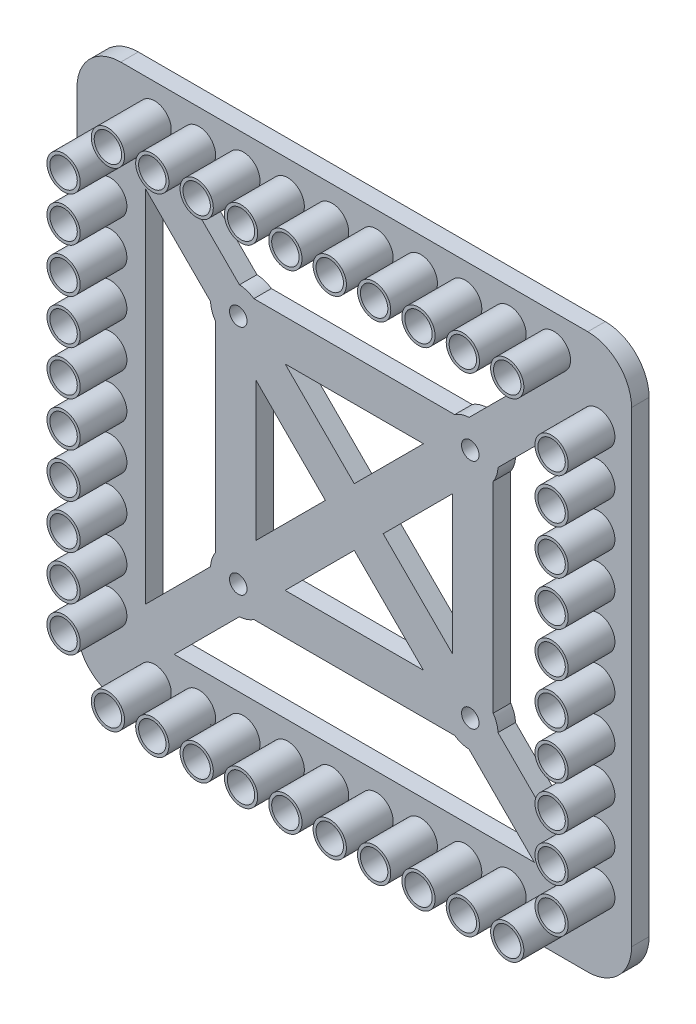
SolidWorks part; units mm, degrees
ref_plane "Front Plane" through (0, 0, 0) normal (0, 0, 1) x (1, 0, 0)
ref_plane "Top Plane" through (0, 0, 0) normal (0, 1, 0) x (1, 0, 0)
ref_plane "Right Plane" through (0, 0, 0) normal (1, 0, 0) x (0, 0, -1)
sketch "Sketch1" plane through (0, 0, 0) normal (0, 0, 1) x (1, 0, 0)
  line L0 (453.6808, -1249.6067) -> (438.4808, -1249.6067) construction
  line L1 (467.0808, -1278.2067) -> (577.0808, -1278.2067) construction
  line L2 (467.0808, -1278.2067) -> (467.0808, -1388.2067) construction
  line L3 (467.0808, -1388.2067) -> (577.0808, -1388.2067) construction
  line L4 (577.0808, -1278.2067) -> (577.0808, -1388.2067) construction
  line L5 (438.4808, -1264.8067) -> (438.4808, -1401.6067) construction
  line L6 (453.6808, -1249.6067) -> (590.4808, -1249.6067) construction
  line L7 (467.0808, -1388.2067) -> (577.0808, -1278.2067) construction
  line L8 (605.6808, -1401.6067) -> (605.6808, -1264.8067) construction
  line L9 (590.4808, -1416.8067) -> (453.6808, -1416.8067) construction
  line L10 (605.6808, -1401.6067) -> (605.6808, -1416.8067) construction
  line L12 (427.0808, -1238.2067) -> (617.0808, -1238.2067) construction
  line L13 (427.0808, -1238.2067) -> (427.0808, -1428.2067) construction
  line L14 (427.0808, -1428.2067) -> (617.0808, -1428.2067) construction
  line L15 (617.0808, -1238.2067) -> (617.0808, -1428.2067) construction
  line L16 (427.0808, -1238.2067) -> (617.0808, -1428.2067) construction
  line L17 (427.0808, -1428.2067) -> (617.0808, -1238.2067) construction
  circle A0 centre (453.6808, -1249.6067) radius 4.7
  circle A1 centre (453.6808, -1249.6067) radius 5.7
  circle A2 centre (468.8808, -1249.6067) radius 4.7
  circle A3 centre (468.8808, -1249.6067) radius 5.7
  circle A4 centre (484.0808, -1249.6067) radius 4.7
  circle A5 centre (484.0808, -1249.6067) radius 5.7
  circle A6 centre (499.2808, -1249.6067) radius 4.7
  circle A7 centre (499.2808, -1249.6067) radius 5.7
  circle A8 centre (514.4808, -1249.6067) radius 4.7
  circle A9 centre (514.4808, -1249.6067) radius 5.7
  circle A10 centre (529.6808, -1249.6067) radius 4.7
  circle A11 centre (529.6808, -1249.6067) radius 5.7
  circle A12 centre (544.8808, -1249.6067) radius 4.7
  circle A13 centre (544.8808, -1249.6067) radius 5.7
  circle A14 centre (560.0808, -1249.6067) radius 4.7
  circle A15 centre (560.0808, -1249.6067) radius 5.7
  circle A16 centre (575.2808, -1249.6067) radius 4.7
  circle A17 centre (575.2808, -1249.6067) radius 5.7
  circle A18 centre (590.4808, -1249.6067) radius 4.7
  circle A19 centre (590.4808, -1249.6067) radius 5.7
  circle A20 centre (438.4808, -1249.6067) radius 4.7 construction
  circle A21 centre (438.4808, -1249.6067) radius 5.7 construction
  circle A22 centre (438.4808, -1264.8067) radius 4.7
  circle A23 centre (438.4808, -1264.8067) radius 5.7
  circle A24 centre (438.4808, -1280.0067) radius 4.7
  circle A25 centre (438.4808, -1280.0067) radius 5.7
  circle A26 centre (438.4808, -1295.2067) radius 4.7
  circle A27 centre (438.4808, -1295.2067) radius 5.7
  circle A28 centre (438.4808, -1310.4067) radius 4.7
  circle A29 centre (438.4808, -1310.4067) radius 5.7
  circle A30 centre (438.4808, -1325.6067) radius 4.7
  circle A31 centre (438.4808, -1325.6067) radius 5.7
  circle A32 centre (438.4808, -1340.8067) radius 4.7
  circle A33 centre (438.4808, -1340.8067) radius 5.7
  circle A34 centre (438.4808, -1356.0067) radius 4.7
  circle A35 centre (438.4808, -1356.0067) radius 5.7
  circle A36 centre (438.4808, -1371.2067) radius 4.7
  circle A37 centre (438.4808, -1371.2067) radius 5.7
  circle A38 centre (438.4808, -1386.4067) radius 4.7
  circle A39 centre (438.4808, -1386.4067) radius 5.7
  circle A40 centre (438.4808, -1401.6067) radius 4.7
  circle A41 centre (438.4808, -1401.6067) radius 5.7
  circle A42 centre (605.6808, -1416.8067) radius 5.7 construction
  circle A43 centre (605.6808, -1416.8067) radius 4.7 construction
  circle A44 centre (453.6808, -1416.8067) radius 5.7
  circle A45 centre (453.6808, -1416.8067) radius 4.7
  circle A46 centre (468.8808, -1416.8067) radius 5.7
  circle A47 centre (468.8808, -1416.8067) radius 4.7
  circle A48 centre (484.0808, -1416.8067) radius 5.7
  circle A49 centre (484.0808, -1416.8067) radius 4.7
  circle A50 centre (499.2808, -1416.8067) radius 5.7
  circle A51 centre (499.2808, -1416.8067) radius 4.7
  circle A52 centre (514.4808, -1416.8067) radius 5.7
  circle A53 centre (514.4808, -1416.8067) radius 4.7
  circle A54 centre (529.6808, -1416.8067) radius 5.7
  circle A55 centre (529.6808, -1416.8067) radius 4.7
  circle A56 centre (544.8808, -1416.8067) radius 5.7
  circle A57 centre (544.8808, -1416.8067) radius 4.7
  circle A58 centre (560.0808, -1416.8067) radius 5.7
  circle A59 centre (560.0808, -1416.8067) radius 4.7
  circle A60 centre (575.2808, -1416.8067) radius 5.7
  circle A61 centre (575.2808, -1416.8067) radius 4.7
  circle A62 centre (590.4808, -1416.8067) radius 5.7
  circle A63 centre (590.4808, -1416.8067) radius 4.7
  circle A64 centre (605.6808, -1264.8067) radius 5.7
  circle A65 centre (605.6808, -1264.8067) radius 4.7
  circle A66 centre (605.6808, -1280.0067) radius 5.7
  circle A67 centre (605.6808, -1280.0067) radius 4.7
  circle A68 centre (605.6808, -1295.2067) radius 5.7
  circle A69 centre (605.6808, -1295.2067) radius 4.7
  circle A70 centre (605.6808, -1310.4067) radius 5.7
  circle A71 centre (605.6808, -1310.4067) radius 4.7
  circle A72 centre (605.6808, -1325.6067) radius 5.7
  circle A73 centre (605.6808, -1325.6067) radius 4.7
  circle A74 centre (605.6808, -1340.8067) radius 5.7
  circle A75 centre (605.6808, -1340.8067) radius 4.7
  circle A76 centre (605.6808, -1356.0067) radius 5.7
  circle A77 centre (605.6808, -1356.0067) radius 4.7
  circle A78 centre (605.6808, -1371.2067) radius 5.7
  circle A79 centre (605.6808, -1371.2067) radius 4.7
  circle A80 centre (605.6808, -1386.4067) radius 5.7
  circle A81 centre (605.6808, -1386.4067) radius 4.7
  circle A82 centre (605.6808, -1401.6067) radius 5.7
  circle A83 centre (605.6808, -1401.6067) radius 4.7
  point P4 (522.0808, -1249.6067)
  point P5 (522.0808, -1278.2067)
  point P10 (438.4808, -1333.2067)
  point P42 (467.0808, -1333.2067)
  point P136 (522.0808, -1333.2067)
  dimension "D5" = 9.4
  dimension "D6" = 1
  dimension "D1" = 110
  dimension "D2" = 110
  dimension "D3" = 190
  dimension "D4" = 136.8
  dimension "D8" = 11
  dimension "D9" = 136.8
  dimension "D10" = 190
  dimension "D7" = 10
extrude "Boss-Extrude1" add sketch "Sketch1" along normal blind 16
sketch "Sketch4" plane through (0, 0, 0) normal (0, 0, 1) x (1, 0, 0)
  line L0 (427.0808, -1238.2067) -> (617.0808, -1428.2067) construction
  line L1 (427.0808, -1428.2067) -> (617.0808, -1428.2067)
  line L2 (427.0808, -1428.2067) -> (427.0808, -1238.2067)
  line L3 (427.0808, -1238.2067) -> (617.0808, -1238.2067)
  line L4 (617.0808, -1428.2067) -> (617.0808, -1238.2067)
  line L5 (427.0808, -1428.2067) -> (617.0808, -1238.2067) construction
  line L6 (427.0808, -1238.2067) -> (617.0808, -1428.2067) construction
  circle A0 centre (438.4808, -1264.8067) radius 4.7 construction
  circle A1 centre (438.4808, -1280.0067) radius 4.7 construction
  circle A2 centre (438.4808, -1295.2067) radius 4.7 construction
  circle A3 centre (438.4808, -1310.4067) radius 4.7 construction
  circle A4 centre (438.4808, -1325.6067) radius 4.7 construction
  circle A5 centre (438.4808, -1340.8067) radius 4.7 construction
  circle A6 centre (438.4808, -1356.0067) radius 4.7 construction
  circle A7 centre (438.4808, -1371.2067) radius 4.7 construction
  circle A8 centre (438.4808, -1386.4067) radius 4.7 construction
  circle A9 centre (438.4808, -1401.6067) radius 4.7 construction
  circle A10 centre (453.6808, -1416.8067) radius 4.7 construction
  circle A11 centre (468.8808, -1416.8067) radius 4.7 construction
  circle A12 centre (484.0808, -1416.8067) radius 4.7 construction
  circle A13 centre (499.2808, -1416.8067) radius 4.7 construction
  circle A14 centre (514.4808, -1416.8067) radius 4.7 construction
  circle A15 centre (529.6808, -1416.8067) radius 4.7 construction
  circle A16 centre (544.8808, -1416.8067) radius 4.7 construction
  circle A17 centre (560.0808, -1416.8067) radius 4.7 construction
  circle A18 centre (575.2808, -1416.8067) radius 4.7 construction
  circle A19 centre (590.4808, -1416.8067) radius 4.7 construction
  circle A20 centre (605.6808, -1401.6067) radius 4.7 construction
  circle A21 centre (605.6808, -1386.4067) radius 4.7 construction
  circle A22 centre (605.6808, -1371.2067) radius 4.7 construction
  circle A23 centre (605.6808, -1356.0067) radius 4.7 construction
  circle A24 centre (605.6808, -1340.8067) radius 4.7 construction
  circle A25 centre (605.6808, -1325.6067) radius 4.7 construction
  circle A26 centre (605.6808, -1310.4067) radius 4.7 construction
  circle A27 centre (605.6808, -1295.2067) radius 4.7 construction
  circle A28 centre (605.6808, -1280.0067) radius 4.7 construction
  circle A29 centre (605.6808, -1264.8067) radius 4.7 construction
  circle A30 centre (590.4808, -1249.6067) radius 4.7 construction
  circle A31 centre (575.2808, -1249.6067) radius 4.7 construction
  circle A32 centre (560.0808, -1249.6067) radius 4.7 construction
  circle A33 centre (544.8808, -1249.6067) radius 4.7 construction
  circle A34 centre (529.6808, -1249.6067) radius 4.7 construction
  circle A35 centre (514.4808, -1249.6067) radius 4.7 construction
  circle A36 centre (499.2808, -1249.6067) radius 4.7 construction
  circle A37 centre (484.0808, -1249.6067) radius 4.7 construction
  circle A38 centre (468.8808, -1249.6067) radius 4.7 construction
  circle A39 centre (453.6808, -1249.6067) radius 4.7 construction
  circle A40 centre (438.4808, -1264.8067) radius 4.7
  circle A41 centre (438.4808, -1280.0067) radius 4.7
  circle A42 centre (438.4808, -1295.2067) radius 4.7
  circle A43 centre (438.4808, -1310.4067) radius 4.7
  circle A44 centre (438.4808, -1325.6067) radius 4.7
  circle A45 centre (438.4808, -1340.8067) radius 4.7
  circle A46 centre (438.4808, -1356.0067) radius 4.7
  circle A47 centre (438.4808, -1371.2067) radius 4.7
  circle A48 centre (438.4808, -1386.4067) radius 4.7
  circle A49 centre (438.4808, -1401.6067) radius 4.7
  circle A50 centre (453.6808, -1416.8067) radius 4.7
  circle A51 centre (468.8808, -1416.8067) radius 4.7
  circle A52 centre (484.0808, -1416.8067) radius 4.7
  circle A53 centre (499.2808, -1416.8067) radius 4.7
  circle A54 centre (514.4808, -1416.8067) radius 4.7
  circle A55 centre (529.6808, -1416.8067) radius 4.7
  circle A56 centre (544.8808, -1416.8067) radius 4.7
  circle A57 centre (560.0808, -1416.8067) radius 4.7
  circle A58 centre (575.2808, -1416.8067) radius 4.7
  circle A59 centre (590.4808, -1416.8067) radius 4.7
  circle A60 centre (605.6808, -1401.6067) radius 4.7
  circle A61 centre (605.6808, -1386.4067) radius 4.7
  circle A62 centre (605.6808, -1371.2067) radius 4.7
  circle A63 centre (605.6808, -1356.0067) radius 4.7
  circle A64 centre (605.6808, -1340.8067) radius 4.7
  circle A65 centre (605.6808, -1325.6067) radius 4.7
  circle A66 centre (605.6808, -1310.4067) radius 4.7
  circle A67 centre (605.6808, -1295.2067) radius 4.7
  circle A68 centre (605.6808, -1280.0067) radius 4.7
  circle A69 centre (605.6808, -1264.8067) radius 4.7
  circle A70 centre (590.4808, -1249.6067) radius 4.7
  circle A71 centre (575.2808, -1249.6067) radius 4.7
  circle A72 centre (560.0808, -1249.6067) radius 4.7
  circle A73 centre (544.8808, -1249.6067) radius 4.7
  circle A74 centre (529.6808, -1249.6067) radius 4.7
  circle A75 centre (514.4808, -1249.6067) radius 4.7
  circle A76 centre (499.2808, -1249.6067) radius 4.7
  circle A77 centre (484.0808, -1249.6067) radius 4.7
  circle A78 centre (468.8808, -1249.6067) radius 4.7
  circle A79 centre (453.6808, -1249.6067) radius 4.7
  point P0 (522.0808, -1333.2067)
extrude "Boss-Extrude3" add sketch "Sketch4" against normal blind 6
sketch "Sketch5" plane through (0, 0, 0) normal (0, 0, 1) x (1, 0, 0)
  circle A0 centre (482.3308, -1293.4567) radius 3
  circle A1 centre (561.8308, -1293.4567) radius 3
  circle A2 centre (561.8308, -1372.9567) radius 3
  circle A3 centre (482.3308, -1372.9567) radius 3
  point P11 (522.0808, -1333.2067)
  dimension "D1" = 6
  dimension "D2" = 4
extrude "Cut-Extrude1" cut sketch "Sketch5" against normal blind 6
sketch "Sketch7" plane through (0, 0, -6) normal (0, 0, -1) x (-1, 0, 0)
  line L6 (-617.0808, -1238.2067) -> (-427.0808, -1428.2067) construction
  line L7 (-617.0808, -1428.2067) -> (-427.0808, -1238.2067) construction
  line L8 (-612.1311, -1433.1565) -> (-422.1311, -1243.1565)
  line L9 (-450.4808, -1404.8067) -> (-593.6808, -1404.8067)
  line L10 (-450.4808, -1404.8067) -> (-450.4808, -1261.6067)
  line L11 (-450.4808, -1261.6067) -> (-593.6808, -1261.6067)
  line L12 (-593.6808, -1404.8067) -> (-593.6808, -1261.6067)
  line L13 (-450.4808, -1404.8067) -> (-593.6808, -1261.6067) construction
  line L14 (-450.4808, -1261.6067) -> (-593.6808, -1404.8067) construction
  line L15 (-474.4808, -1380.8067) -> (-569.6808, -1380.8067)
  line L16 (-474.4808, -1380.8067) -> (-474.4808, -1285.6067)
  line L17 (-474.4808, -1285.6067) -> (-569.6808, -1285.6067)
  line L18 (-569.6808, -1380.8067) -> (-569.6808, -1285.6067)
  line L19 (-474.4808, -1380.8067) -> (-569.6808, -1285.6067) construction
  line L20 (-474.4808, -1285.6067) -> (-569.6808, -1380.8067) construction
  line L21 (-622.0306, -1243.1565) -> (-432.0306, -1433.1565)
  line L22 (-622.0306, -1423.257) -> (-432.0306, -1233.257)
  line L23 (-612.1311, -1233.257) -> (-422.1311, -1423.257)
  line L24 (-467.0808, -1388.2067) -> (-577.0808, -1278.2067) construction
  line L26 (-488.4808, -1366.8067) -> (-555.6808, -1366.8067)
  line L27 (-488.4808, -1366.8067) -> (-488.4808, -1299.6067)
  line L28 (-488.4808, -1299.6067) -> (-555.6808, -1299.6067)
  line L29 (-555.6808, -1366.8067) -> (-555.6808, -1299.6067)
  line L30 (-488.4808, -1366.8067) -> (-555.6808, -1299.6067) construction
  line L31 (-488.4808, -1299.6067) -> (-555.6808, -1366.8067) construction
  circle A0 centre (-605.6808, -1401.6067) radius 5.7 construction
  point P4 (-522.0808, -1333.2067)
  point P18 (-522.0808, -1333.2067)
  point P37 (-522.0808, -1333.2067)
  dimension "D1" = 12
  dimension "D2" = 12
  dimension "D3" = 12
  dimension "D6" = 14
  dimension "D7" = 24
  dimension "D4" = 7
  dimension "D5" = 7
extrude "Cut-Extrude2" cut sketch "Sketch7" against normal blind 6 contours L11 L23 L17 L22 | L22 L28 L23 | L29 L22 L21 | L26 L21 L8 | L23 L27 L8 | L16 L23 L10 L8 | L21 L15 L8 L9 | L12 L22 L18 L21
sketch "Sketch8" plane through (0, 0, 0) normal (0, 0, 1) x (1, 0, 0)
  circle A0 centre (482.3308, -1372.9567) radius 9.5
  circle A1 centre (561.8308, -1372.9567) radius 9.5
  circle A2 centre (561.8308, -1293.4567) radius 9.5
  circle A3 centre (482.3308, -1293.4567) radius 9.5
  circle A4 centre (482.3308, -1293.4567) radius 3
  circle A5 centre (561.8308, -1293.4567) radius 3.1094
  circle A6 centre (561.8308, -1372.9567) radius 3
  circle A7 centre (482.3308, -1372.9567) radius 3
  dimension "D1" = 19
  dimension "D2" = 19
  dimension "D3" = 19
  dimension "D4" = 19
extrude "Boss-Extrude4" add sketch "Sketch8" against normal blind 6
fillet "Fillet1" radius 15 4 edges at (617.0808, -1428.2067, -3) (427.0808, -1428.2067, -3) (427.0808, -1238.2067, -3) (617.0808, -1238.2067, -3)
